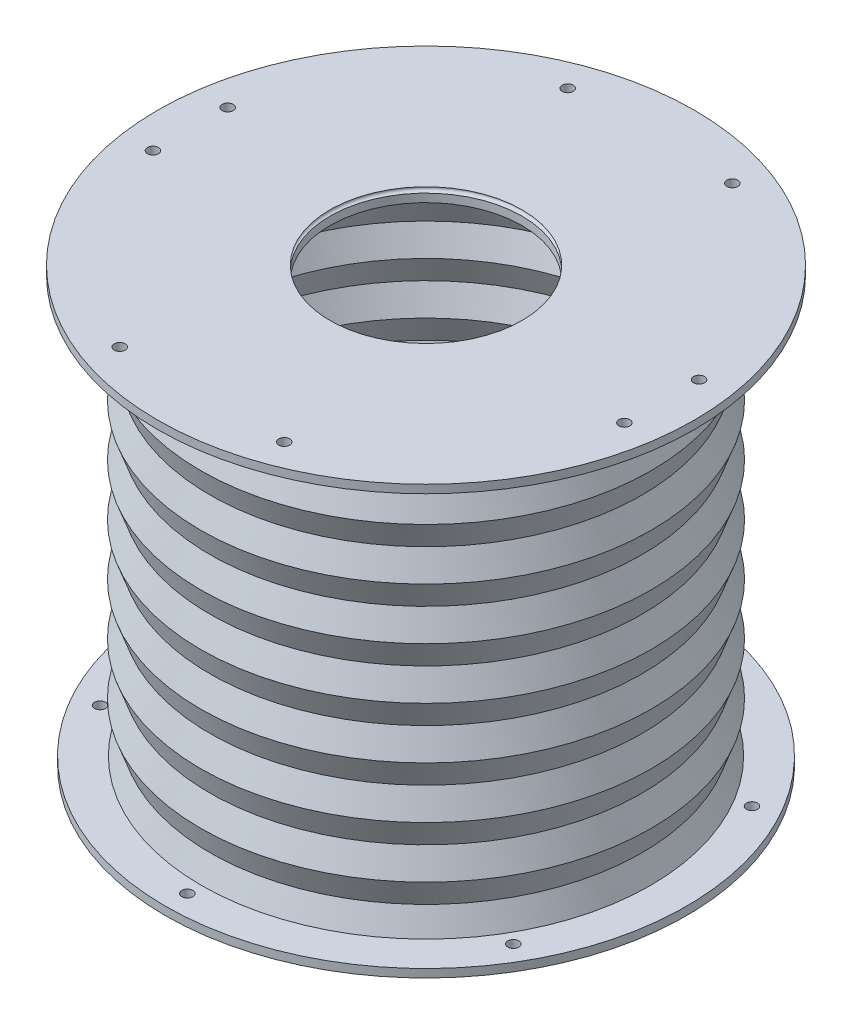
SolidWorks part; units mm, degrees
material "Silicon Rubber"
ref_plane "Front Plane" through (0, 0, 0) normal (0, 0, 1) x (1, 0, 0)
ref_plane "Top Plane" through (0, 0, 0) normal (0, 1, 0) x (1, 0, 0)
ref_plane "Right Plane" through (0, 0, 0) normal (1, 0, 0) x (0, 0, -1)
sketch "Sketch1" plane through (0, 0, 0) normal (0, 0, 1) x (1, 0, 0)
  line L1 (80, 1.1618) -> (76.6185, 10.5728)
  line L2 (76.6185, 10.5728) -> (80, 19.9837)
  line L3 (80, 19.9837) -> (76.6185, 29.3946)
  line L4 (76.6185, 29.3946) -> (80, 38.8055)
  line L5 (80, 38.8055) -> (76.6185, 48.2164)
  line L6 (76.6185, 48.2164) -> (80, 57.6273)
  line L7 (80, 57.6273) -> (76.6185, 67.0382)
  line L8 (76.6185, 67.0382) -> (80, 76.4492)
  line L9 (80, 76.4492) -> (76.6185, 85.8601)
  line L10 (76.6185, 85.8601) -> (80, 95.271)
  line L11 (80, 95.271) -> (76.6185, 104.6819)
  line L12 (76.6185, 104.6819) -> (80, 114.0928)
  line L13 (80, 114.0928) -> (76.6185, 123.5037)
  line L14 (76.6185, 123.5037) -> (80, 132.9146)
  line L36 (81.8822, 1.8382) -> (78.7437, 10.5728)
  line L37 (78.7437, 10.5728) -> (82.1252, 19.9837)
  line L41 (82.1252, 19.9837) -> (78.7437, 29.3946)
  line L42 (78.7437, 29.3946) -> (82.1252, 38.8055)
  line L43 (80, 132.9146) -> (76.6185, 142.3255)
  line L44 (76.6185, 142.3255) -> (80, 151.7365)
  line L45 (82.1252, 38.8055) -> (78.7437, 48.2164)
  line L46 (78.7437, 48.2164) -> (82.1252, 57.6273)
  line L47 (82.1252, 57.6273) -> (78.7437, 67.0382)
  line L48 (78.7437, 67.0382) -> (82.1252, 76.4492)
  line L49 (82.1252, 76.4492) -> (78.7437, 85.8601)
  line L50 (78.7437, 85.8601) -> (82.1252, 95.271)
  line L51 (82.1252, 95.271) -> (78.7437, 104.6819)
  line L52 (78.7437, 104.6819) -> (82.1252, 114.0928)
  line L53 (82.1252, 114.0928) -> (78.7437, 123.5037)
  line L54 (78.7437, 123.5037) -> (82.1252, 132.9146)
  line L55 (82.1252, 132.9146) -> (78.7437, 142.3255)
  line L56 (78.7437, 142.3255) -> (82.8438, 153.7365)
  line L63 (82.8438, 153.7365) -> (97.8438, 153.7365)
  line L64 (97.8438, 153.7365) -> (97.8438, 156.7365)
  line L65 (97.8438, 156.7365) -> (34.9959, 156.7365)
  line L66 (34.9959, 154.7365) -> (34.9959, 151.7365)
  line L68 (82.8438, 153.7365) -> (41.6243, 153.7365) construction
  line L69 (80, 151.7365) -> (41.6243, 151.7365) construction
  line L72 (0, 1.1618) -> (80, 1.1618) construction
  line L73 (81.8822, 1.8382) -> (95, 1.8382)
  line L74 (95, 1.8382) -> (95, -1.1618)
  line L75 (95, -1.1618) -> (0, -1.1618) construction
  line L76 (0, 1.1618) -> (0, -1.1618) construction
  line L77 (0, 0) -> (0, 156.2642) construction
  line L78 (34.9959, 151.7365) -> (80, 151.7365)
  line L79 (80, 1.1618) -> (65, 1.1618)
  line L80 (65, 1.1618) -> (65, -1.1618)
  line L81 (65, -1.1618) -> (95, -1.1618)
  arc A1 (34.9959, 154.7365) -> (34.9959, 156.7365) centre (34.9959, 155.7365) ccw
  point P49 (0, 0)
  dimension "D1" = 2
  dimension "D2" = 10
  dimension "D4" = 2
  dimension "D5" = 5
  dimension "D6" = 34.9959
  dimension "D7" = 15
  dimension "D8" = 3
  dimension "D9" = 3
  dimension "D10" = 80
  dimension "D11" = 95
  dimension "D12" = 15
  dimension "D3" = 8
revolve "Revolve4" add sketch "Sketch1" angle 360 about L77
sketch "Sketch2" plane through (0, 156.7365, 0) normal (0, 1, 0) x (1, 0, 0)
  line L0 (-85.9289, 13.6098) -> (85.9289, -13.6098) construction
  line L1 (85.9289, 13.6098) -> (-85.9289, -13.6098) construction
  circle A6 centre (0, 0) radius 87 construction
  circle A7 centre (-85.9289, 13.6098) radius 2
  circle A8 centre (-85.9289, -13.6098) radius 2
  circle A9 centre (85.9289, 13.6098) radius 2
  circle A10 centre (85.9289, -13.6098) radius 2
  circle A11 centre (-30, 81.6639) radius 2
  circle A12 centre (30, 81.6639) radius 2
  circle A13 centre (30, -81.6639) radius 2
  circle A14 centre (-30, -81.6639) radius 2
  dimension "D1" = 174
  dimension "D3" = 4
  dimension "D2" = 60
  dimension "D4" = 18
extrude "Cut-Extrude1" cut sketch "Sketch2" against normal up to next
sketch "Sketch3" plane through (0, -1.1618, 0) normal (0, -1, 0) x (1, 0, 0)
  circle A0 centre (0, 87) radius 2
  circle A1 centre (75.3442, 43.5) radius 2
  circle A2 centre (75.3442, -43.5) radius 2
  circle A3 centre (0, -87) radius 2
  circle A4 centre (-75.3442, -43.5) radius 2
  circle A5 centre (-75.3442, 43.5) radius 2
  point P15 (0, 0)
  dimension "D1" = 4
  dimension "D2" = 87
  dimension "D3" = 6
extrude "Cut-Extrude2" cut sketch "Sketch3" against normal up to next
